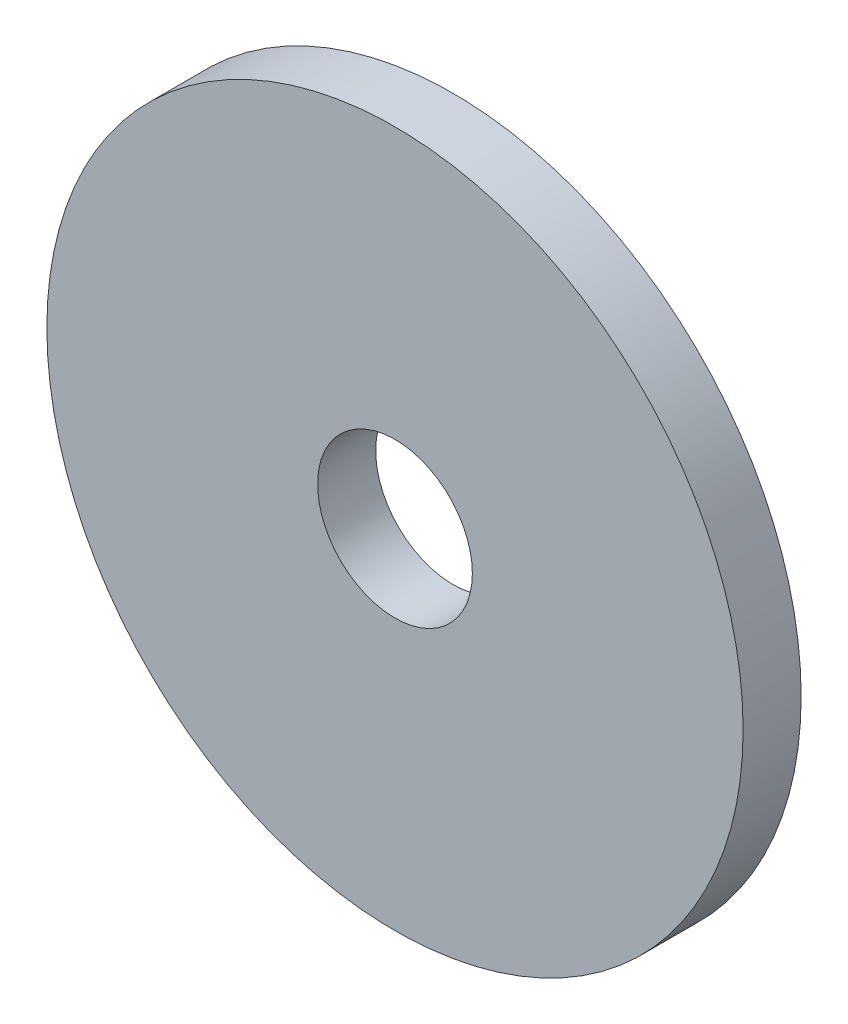
SolidWorks part; units mm, degrees
ref_plane "Piano frontale" through (0, 0, 0) normal (0, 0, 1) x (1, 0, 0)
ref_plane "Piano superiore" through (0, 0, 0) normal (0, 1, 0) x (1, 0, 0)
ref_plane "Piano destro" through (0, 0, 0) normal (1, 0, 0) x (0, 0, -1)
sketch "Schizzo1" plane through (0, 0, 0) normal (0, 0, 1) x (1, 0, 0)
  circle A0 centre (0, 0) radius 4
  circle A1 centre (0, 0) radius 18
  dimension "D1" = 36
  dimension "D2" = 8
extrude "Estrusione-Estrusione1" add sketch "Schizzo1" along normal blind 3
